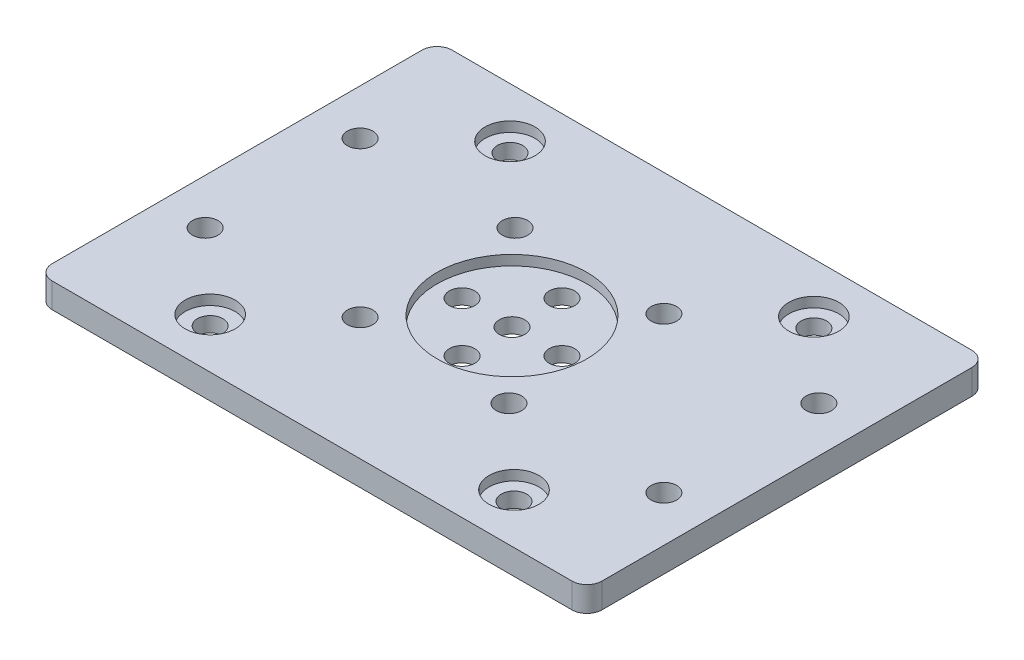
SolidWorks part; units mm, degrees
material "6061-T6 (SS)"
ref_plane "Front Plane" through (0, 0, 0) normal (0, 0, 1) x (1, 0, 0)
ref_plane "Top Plane" through (0, 0, 0) normal (0, 1, 0) x (1, 0, 0)
ref_plane "Right Plane" through (0, 0, 0) normal (1, 0, 0) x (0, 0, -1)
sketch "Sketch1" plane through (0, 0, 0) normal (0, 1, 0) x (1, 0, 0)
  line L0 (0, 0) -> (55, 0) construction
  line L1 (52, -40) -> (-52, -40)
  line L2 (55, -37) -> (55, 37)
  line L3 (52, 40) -> (-52, 40)
  line L4 (-55, -37) -> (-55, 37)
  line L5 (0, 40) -> (0, 0) construction
  arc A0 (-52, -40) -> (-55, -37) centre (-52, -37) cw
  arc A1 (52, -40) -> (55, -37) centre (52, -37) ccw
  arc A2 (55, 37) -> (52, 40) centre (52, 37) ccw
  arc A3 (-52, 40) -> (-55, 37) centre (-52, 37) ccw
  circle A4 centre (-30.395, 30) radius 2.55
  circle A5 centre (0, 10) radius 2.55
  circle A6 centre (0, 0) radius 2.55
  circle A7 centre (10, 0) radius 2.55
  circle A8 centre (-10, 0) radius 2.55
  circle A16 centre (-45.895, 15.5) radius 2.55
  circle A23 centre (30.4, 30) radius 2.55
  circle A30 centre (0, -10) radius 2.55
  circle A33 centre (-14.895, 15.5) radius 2.55
  circle A43 centre (14.895, 15.5) radius 2.55
  circle A46 centre (45.895, 15.5) radius 2.55
  circle A53 centre (30.4, -30) radius 2.55
  circle A54 centre (45.895, -15.5) radius 2.55
  circle A57 centre (14.895, -15.5) radius 2.55
  circle A60 centre (-14.895, -15.5) radius 2.55
  circle A63 centre (-45.895, -15.5) radius 2.55
  circle A66 centre (-30.395, -30) radius 2.55
  point P0 (0, 0)
  dimension "D2" = 3
  dimension "D3" = 5.1
  dimension "D5" = 60
  dimension "D10" = 10
  dimension "D1" = 80
  dimension "D4" = 10
  dimension "D6" = 15.5
  dimension "D8" = 31
  dimension "D9" = 110
  dimension "D11" = 60
  dimension "D12" = 30.395
  dimension "D13" = 30.4
extrude "Boss-Extrude1" add sketch "Sketch1" along normal blind 5
sketch "草圖1" plane through (0, 5, 0) normal (0, 1, 0) x (1, 0, 0)
  circle A0 centre (-30.395, -30) radius 5
  circle A1 centre (-30.395, 30) radius 5
  circle A2 centre (30.4, -30) radius 5
  circle A3 centre (30.4, 30) radius 5
  circle A4 centre (0, 0) radius 15
extrude "除料-伸長1" cut sketch "草圖1" against normal blind 2
